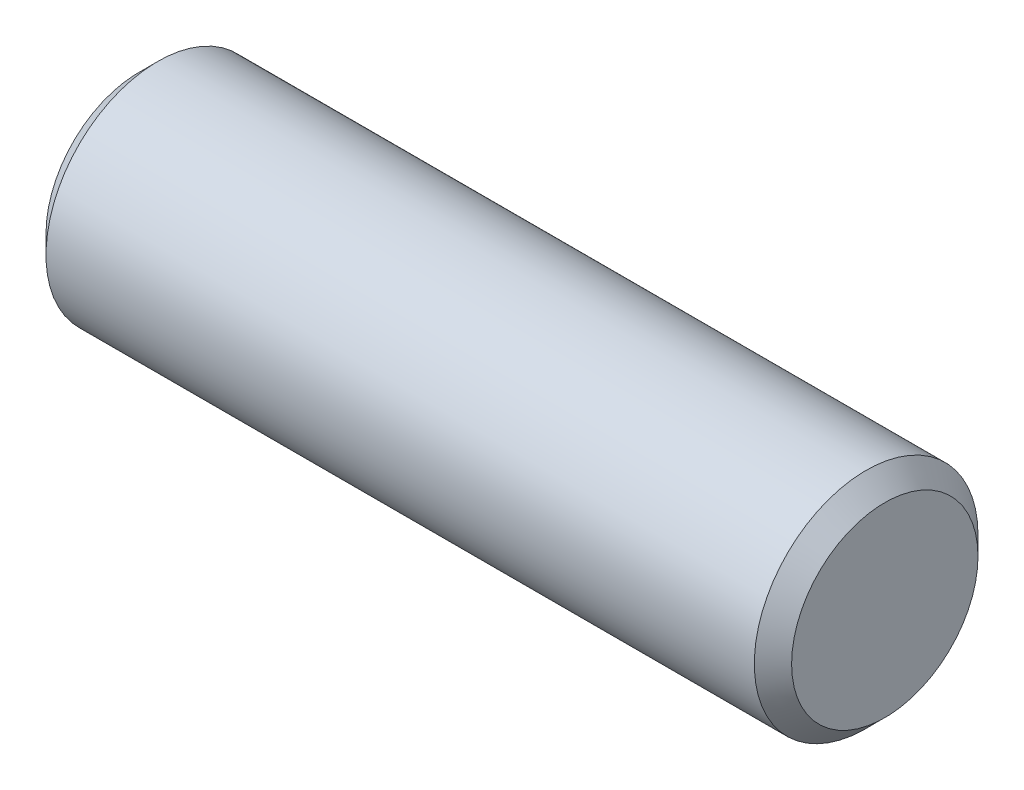
SolidWorks part; units mm, degrees
ref_plane "Front Plane" through (0, 0, 0) normal (0, 0, 1) x (1, 0, 0)
ref_plane "Top Plane" through (0, 0, 0) normal (0, 1, 0) x (1, 0, 0)
ref_plane "Right Plane" through (0, 0, 0) normal (1, 0, 0) x (0, 0, -1)
sketch "Sketch1" plane through (0, 0, 0) normal (1, 0, 0) x (0, 0, -1)
  circle A0 centre (0, 0) radius 1.5
  dimension "D1" = 3
extrude "Boss-Extrude1" add sketch "Sketch1" along normal blind 10
chamfer "Chamfer1" distance 0.25 angle 45 2 edges at (0, 0, -1.5) (10, 0, -1.5)
